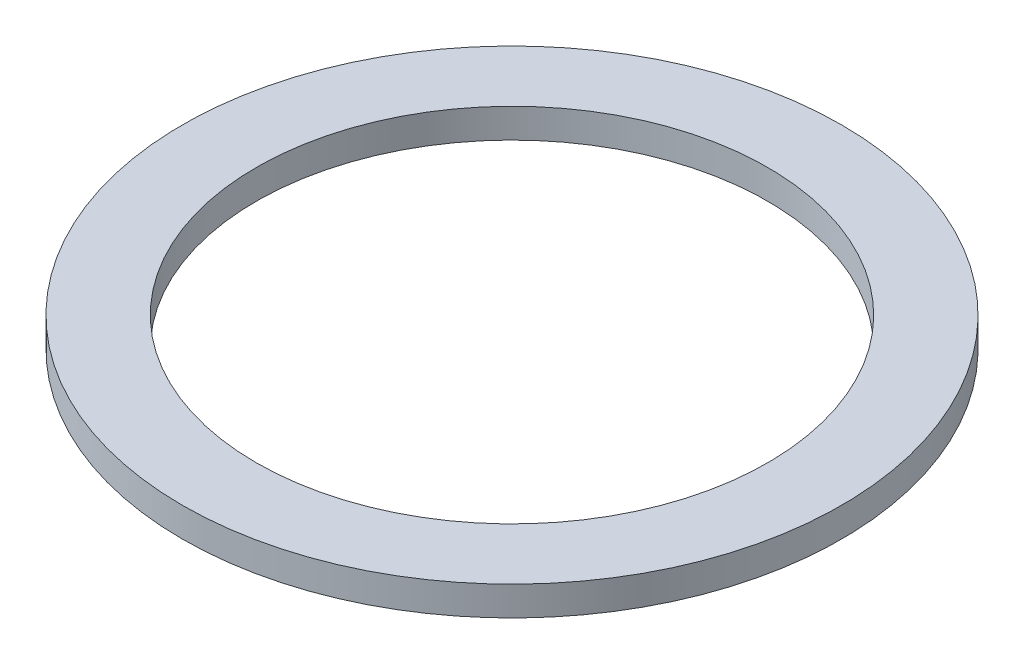
SolidWorks part; units mm, degrees
ref_plane "Front Plane" through (0, 0, 0) normal (0, 0, 1) x (1, 0, 0)
ref_plane "Top Plane" through (0, 0, 0) normal (0, 1, 0) x (1, 0, 0)
ref_plane "Right Plane" through (0, 0, 0) normal (1, 0, 0) x (0, 0, -1)
sketch "Sketch1" plane through (0, 0, 0) normal (0, 1, 0) x (1, 0, 0)
  circle A0 centre (0, 0) radius 6.985
  circle A1 centre (0, 0) radius 9
  dimension "D1" = 13.97
  dimension "D2" = 18
extrude "Boss-Extrude1" add sketch "Sketch1" along normal blind 0.8
